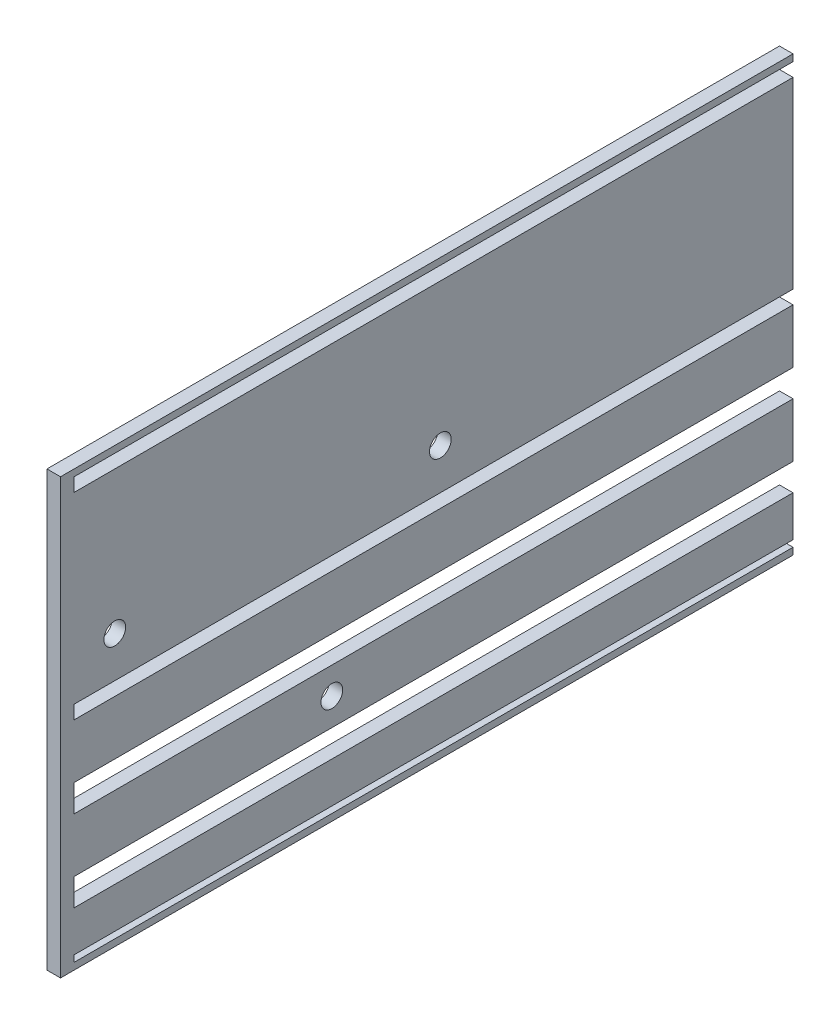
SolidWorks part; units mm, degrees
ref_plane "Front Plane" through (0, 0, 0) normal (0, 0, 1) x (1, 0, 0)
ref_plane "Top Plane" through (0, 0, 0) normal (0, 1, 0) x (1, 0, 0)
ref_plane "Right Plane" through (0, 0, 0) normal (1, 0, 0) x (0, 0, -1)
sketch "Sketch1" plane through (0, 0, 0) normal (1, 0, 0) x (0, 0, -1)
  line L0 (31.4036, -50.2613) -> (59.3698, -50.2613)
  line L1 (-118.3416, 44.9887) -> (53.1084, 44.9887)
  line L2 (-118.3416, 44.9887) -> (-118.3416, -56.6113)
  line L3 (-118.3416, -56.6113) -> (53.1084, -56.6113)
  line L4 (53.1084, 44.9887) -> (53.1084, -56.6113)
  line L5 (-115.1666, 43.4012) -> (63.73, 43.4012)
  line L6 (-115.1666, 43.4012) -> (-115.1666, 40.2262)
  line L7 (-115.1666, 40.2262) -> (63.73, 40.2262)
  line L8 (63.73, 43.4012) -> (63.73, 40.2262)
  line L9 (-115.1666, -2.7048) -> (63.73, -2.7048)
  line L10 (-115.1666, -2.7048) -> (-115.1666, -5.8798)
  line L11 (-115.1666, -5.8798) -> (63.73, -5.8798)
  line L12 (63.73, -2.7048) -> (63.73, -5.8798)
  line L13 (-115.1666, -18.5798) -> (66.442, -18.5798)
  line L14 (-115.1666, -18.5798) -> (-115.1666, -24.9298)
  line L15 (-115.1666, -24.9298) -> (66.442, -24.9298)
  line L16 (66.442, -18.5798) -> (66.442, -24.9298)
  line L17 (-115.1666, -37.6298) -> (63.73, -37.6298)
  line L18 (-115.1666, -37.6298) -> (-115.1666, -43.9798)
  line L19 (-115.1666, -43.9798) -> (63.73, -43.9798)
  line L20 (63.73, -37.6298) -> (63.73, -43.9798)
  line L21 (-115.1666, -53.5048) -> (63.73, -53.5048)
  line L22 (-115.1666, -53.5048) -> (-115.1666, -55.0238)
  line L23 (-115.1666, -55.0238) -> (63.73, -55.0238)
  line L24 (63.73, -53.5048) -> (63.73, -55.0238)
  line L25 (35.0387, 25.9387) -> (59.3698, 25.9387)
  circle A0 centre (-105.6416, 6.8887) radius 2.54
  circle A1 centre (-29.4416, 6.8887) radius 2.54
  circle A2 centre (-54.8416, -31.2113) radius 2.54
  dimension "D20" = 5.08
  dimension "D21" = 5.08
  dimension "D22" = 5.08
  dimension "D1" = 101.6
  dimension "D2" = 171.45
  dimension "D3" = 6.35
  dimension "D4" = 6.35
  dimension "D5" = 3.175
  dimension "D6" = 3.175
  dimension "D7" = 1.5875
  dimension "D8" = 1.5875
  dimension "D9" = 9.525
  dimension "D10" = 12.7
  dimension "D11" = 12.7
  dimension "D12" = 3.175
  dimension "D13" = 3.175
  dimension "D14" = 3.175
  dimension "D15" = 3.175
  dimension "D16" = 3.175
  dimension "D17" = 1.5189
  dimension "D18" = 19.05
  dimension "D19" = 6.35
  dimension "D23" = 76.2
  dimension "D24" = 12.7
  dimension "D25" = 38.1
  dimension "D26" = 25.4
  dimension "D27" = 63.5
extrude "Boss-Extrude1" add sketch "Sketch1" along normal blind 3.175
